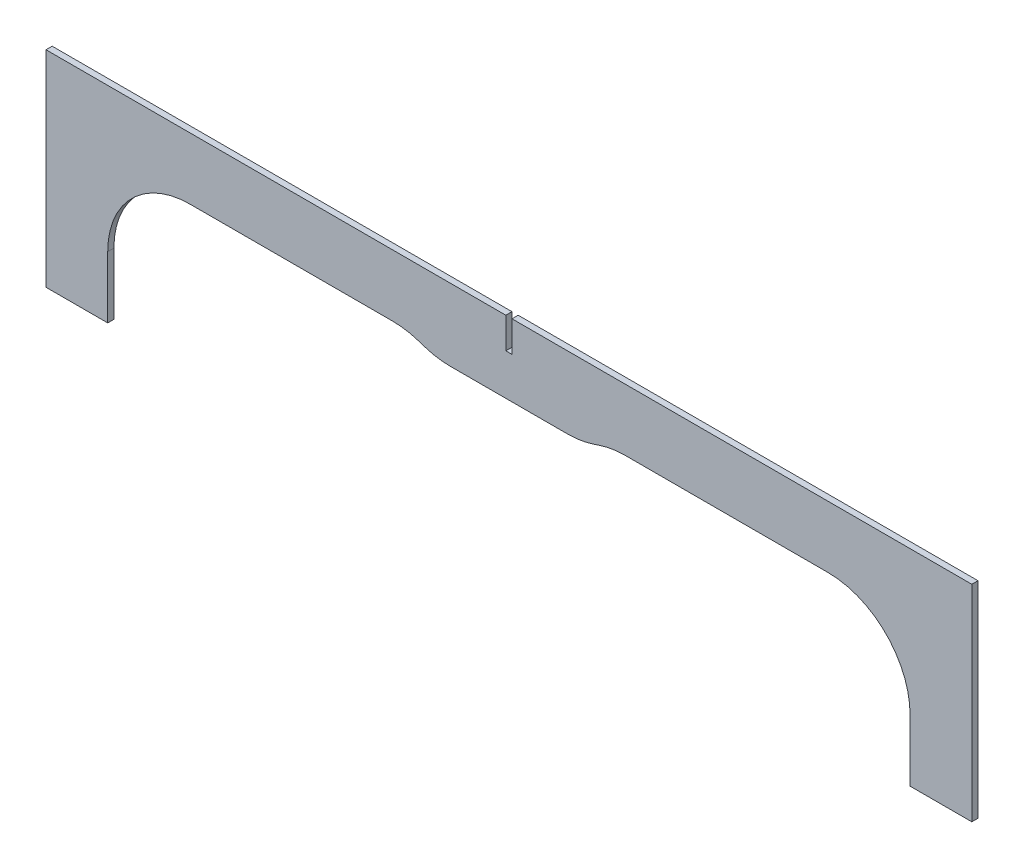
SolidWorks part; units mm, degrees
ref_plane "Front Plane" through (0, 0, 0) normal (0, 0, 1) x (1, 0, 0)
ref_plane "Top Plane" through (0, 0, 0) normal (0, 1, 0) x (1, 0, 0)
ref_plane "Right Plane" through (0, 0, 0) normal (1, 0, 0) x (0, 0, -1)
sketch "Sketch1" plane through (0, 0, 0) normal (0, 0, 1) x (1, 0, 0)
  line L0 (0, 0) -> (0, 100)
  line L1 (0, 100) -> (223.5, 100)
  line L2 (223.5, 100) -> (223.5, 85)
  line L3 (223.5, 85) -> (226.5, 85)
  line L4 (226.5, 85) -> (226.5, 100)
  line L5 (226.5, 100) -> (450, 100)
  line L6 (450, 100) -> (450, 0)
  line L7 (450, 0) -> (420, 0)
  line L8 (420, 0) -> (420, 70)
  line L9 (420, 70) -> (275, 70)
  line L10 (275, 70) -> (260, 65)
  line L11 (260, 65) -> (190, 65)
  line L12 (190, 65) -> (175, 70)
  line L13 (175, 70) -> (30, 70)
  line L14 (30, 70) -> (30, 0)
  line L15 (30, 0) -> (0, 0)
  line L16 (225, 85) -> (225, 65) construction
  dimension "D1" = 450
  dimension "D2" = 100
  dimension "D3" = 100
  dimension "D4" = 30
  dimension "D5" = 30
  dimension "D6" = 3
  dimension "D7" = 30
  dimension "D8" = 30
  dimension "D9" = 223.5
  dimension "D10" = 15
  dimension "D11" = 70
  dimension "D12" = 20
  dimension "D13" = 15
extrude "Boss-Extrude1" add sketch "Sketch1" along normal blind 3
fillet "Fillet1" radius 40 6 edges at (30, 70, 1.5) (190, 65, 1.5) (175, 70, 1.5) (260, 65, 1.5) (275, 70, 1.5) (420, 70, 1.5)
equation "\"D9@Sketch1\"=\"D1@Sketch1\"/2-\"D6@Sketch1\"/2"
